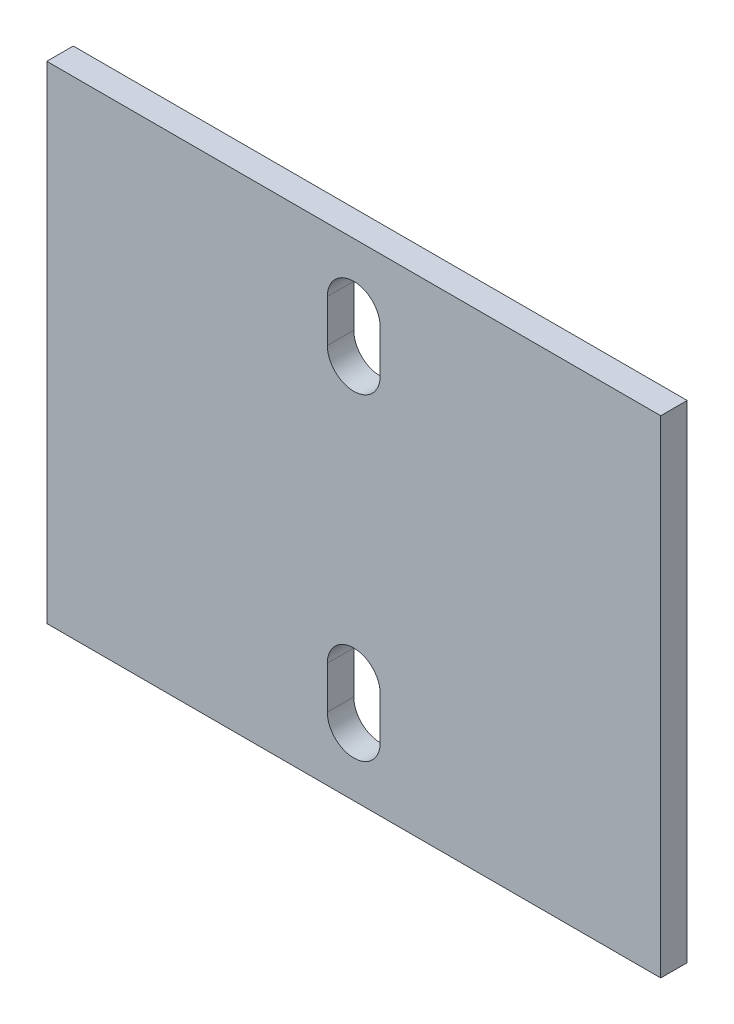
SolidWorks part; units mm, degrees
ref_plane "Front Plane" through (0, 0, 0) normal (0, 0, 1) x (1, 0, 0)
ref_plane "Top Plane" through (0, 0, 0) normal (0, 1, 0) x (1, 0, 0)
ref_plane "Right Plane" through (0, 0, 0) normal (1, 0, 0) x (0, 0, -1)
sketch "Sketch1" plane through (0, 0, 0) normal (0, 0, 1) x (1, 0, 0)
  line L0 (0, 7.5) -> (0, -7.5) construction
  line L1 (-14.5, 11.5) -> (14.5, 11.5)
  line L2 (-14.5, 11.5) -> (-14.5, -11.5)
  line L3 (-14.5, -11.5) -> (14.5, -11.5)
  line L4 (14.5, 11.5) -> (14.5, -11.5)
  line L5 (-14.5, 11.5) -> (14.5, -11.5) construction
  line L6 (-14.5, -11.5) -> (14.5, 11.5) construction
  line L7 (0, 6.5) -> (0, 8.5) construction
  line L8 (-1.25, 6.5) -> (-1.25, 8.5)
  line L9 (1.25, 6.5) -> (1.25, 8.5)
  line L10 (0, -6.5) -> (0, -8.5) construction
  line L11 (1.25, -6.5) -> (1.25, -8.5)
  line L12 (-1.25, -6.5) -> (-1.25, -8.5)
  arc A0 (-1.25, 6.5) -> (1.25, 6.5) centre (0, 6.5) ccw
  arc A1 (1.25, 8.5) -> (-1.25, 8.5) centre (0, 8.5) ccw
  arc A2 (1.25, -6.5) -> (-1.25, -6.5) centre (0, -6.5) ccw
  arc A3 (-1.25, -8.5) -> (1.25, -8.5) centre (0, -8.5) ccw
  point P0 (0, 0)
  point P9 (0, 0)
  point P11 (0, 7.5)
  point P17 (0, -7.5)
  point P23 (0, 4.9744)
  dimension "D4" = 1.25
  dimension "D1" = 29
  dimension "D2" = 15
  dimension "D3" = 2
  dimension "D5" = 4
extrude "Boss-Extrude1" add sketch "Sketch1" along normal blind 1.25
